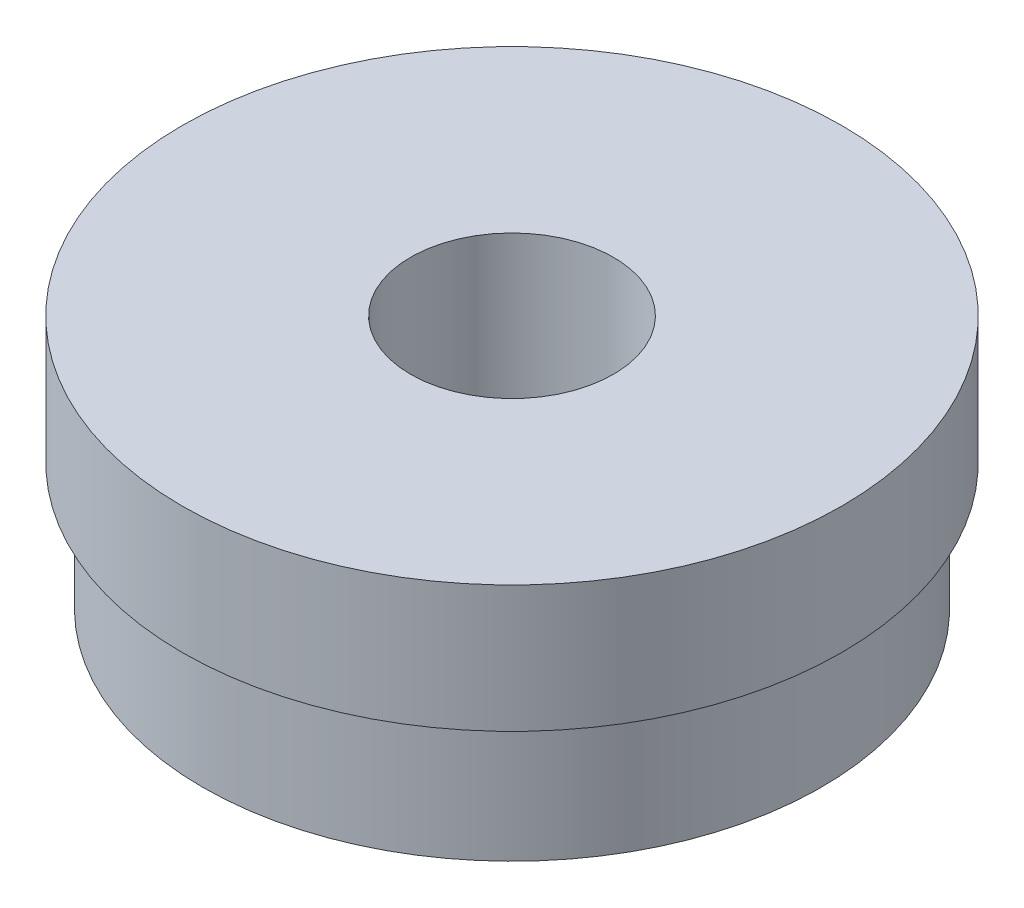
SolidWorks part; units mm, degrees
ref_plane "Front Plane" through (0, 0, 0) normal (0, 0, 1) x (1, 0, 0)
ref_plane "Top Plane" through (0, 0, 0) normal (0, 1, 0) x (1, 0, 0)
ref_plane "Right Plane" through (0, 0, 0) normal (1, 0, 0) x (0, 0, -1)
sketch "Sketch1" plane through (0, 0, 0) normal (0, 0, 1) x (1, 0, 0)
  line L0 (0, 53.1607) -> (0, -48.5179) construction
  line L1 (0, 48.0536) -> (65, 48.0536)
  line L2 (65, 48.0536) -> (65, 23.0536)
  line L3 (65, 23.0536) -> (61, 23.0536)
  line L4 (61, 23.0536) -> (61, -1.9464)
  line L5 (61, -1.9464) -> (0, -1.9464)
  line L6 (0, -1.9464) -> (0, 48.0536)
  dimension "D1" = 65
  dimension "D2" = 25
  dimension "D3" = 25
  dimension "D4" = 4
revolve "Revolve1" add sketch "Sketch1" angle 360 about L0
sketch "Sketch2" plane through (0, 48.0536, 0) normal (0, 1, 0) x (1, 0, 0)
  circle A0 centre (0, 0) radius 20
  dimension "D1" = 40
extrude "Cut-Extrude1" cut sketch "Sketch2" against normal through all
